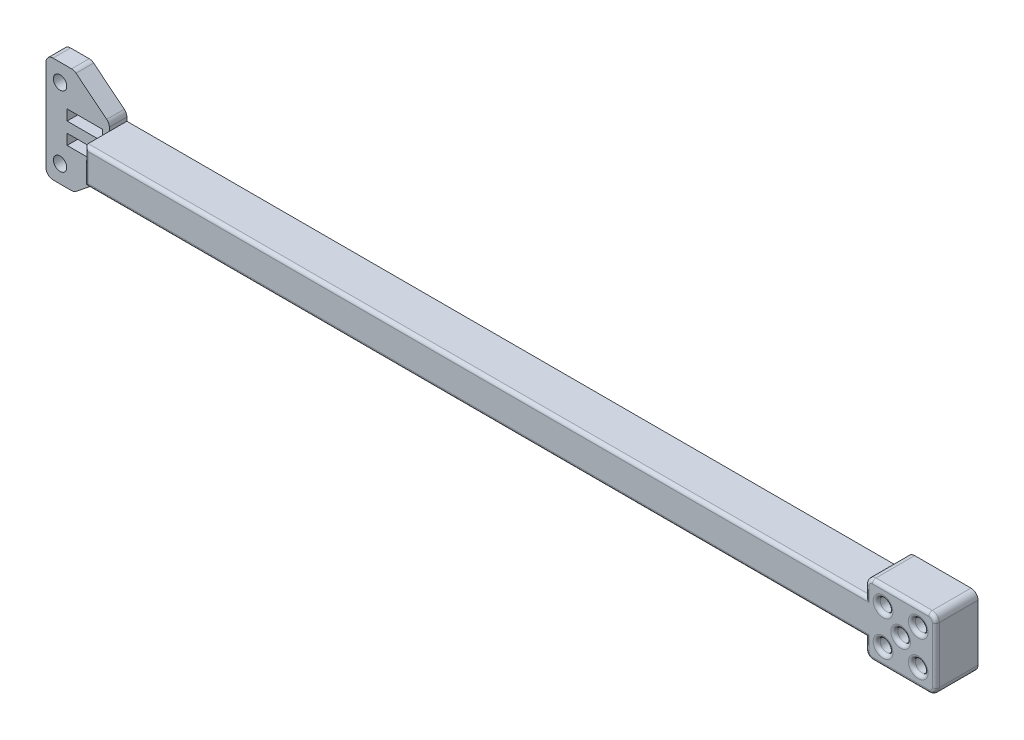
SolidWorks part; units mm, degrees
ref_plane "Front Plane" through (0, 0, 0) normal (0, 0, 1) x (1, 0, 0)
ref_plane "Top Plane" through (0, 0, 0) normal (0, 1, 0) x (1, 0, 0)
ref_plane "Right Plane" through (0, 0, 0) normal (1, 0, 0) x (0, 0, -1)
sketch "Sketch1" plane through (0, 0, 0) normal (0, 0, 1) x (1, 0, 0)
  line L0 (-140.97, -6.2865) -> (-140.97, -8.8265)
  line L1 (-140.97, -6.2865) -> (140.97, -6.2865)
  line L3 (-140.97, 6.2865) -> (140.97, 6.2865)
  line L5 (-163.83, 0) -> (153.67, 0) construction
  line L6 (-143.51, -1.905) -> (-143.51, -5.715)
  line L7 (-153.67, 19.05) -> (-163.83, 19.05)
  line L8 (-140.97, 8.8265) -> (-140.97, 6.2865)
  line L9 (-153.67, -19.05) -> (-163.83, -19.05)
  line L10 (-163.83, 19.05) -> (-163.83, -19.05)
  line L11 (-156.21, 1.905) -> (-143.51, 1.905)
  line L12 (-156.21, 1.905) -> (-156.21, 5.715)
  line L13 (-156.21, 5.715) -> (-143.51, 5.715)
  line L14 (-143.51, 1.905) -> (-143.51, 5.715)
  line L15 (-156.21, -5.715) -> (-143.51, -5.715)
  line L16 (-156.21, -1.905) -> (-143.51, -1.905)
  line L17 (-156.21, -1.905) -> (-156.21, -5.715)
  line L18 (-140.97, -8.8265) -> (-153.67, -19.05)
  line L19 (-140.97, 8.8265) -> (-153.67, 19.05)
  line L21 (166.37, -12.7) -> (140.97, -12.7)
  line L22 (166.37, -12.7) -> (166.37, 12.7)
  line L23 (166.37, 12.7) -> (140.97, 12.7)
  line L24 (140.97, -12.7) -> (140.97, 12.7)
  line L25 (166.37, -12.7) -> (140.97, 12.7) construction
  line L26 (166.37, 12.7) -> (140.97, -12.7) construction
  circle A1 centre (-158.75, -12.7) radius 2.413
  circle A4 centre (-158.75, 12.7) radius 2.413
  circle A5 centre (147.32, -6.35) radius 2.286
  circle A6 centre (160.02, -6.35) radius 2.286
  circle A7 centre (160.02, 6.35) radius 2.286
  circle A8 centre (147.32, 6.35) radius 2.286
  circle A9 centre (153.67, 0) radius 2.286
  point P0 (0, 0)
  point P4 (0, 6.2865)
  point P15 (-158.75, -19.05)
  point P18 (-163.83, 0)
  dimension "D3" = 4.826
  dimension "D8" = 6.35
  dimension "D9" = 25.4
  dimension "D19" = 4.572
  dimension "D2" = 38.1
  dimension "D4" = 12.7
  dimension "D5" = 10.16
  dimension "D6" = 317.5
  dimension "D7" = 12.573
  dimension "D10" = 5.08
  dimension "D11" = 3.81
  dimension "D12" = 12.7
  dimension "D13" = 1.905
  dimension "D14" = 7.62
  dimension "D15" = 2.54
  dimension "D16" = 22.86
  dimension "D17" = 25.4
  dimension "D18" = 6.35
  dimension "D20" = 2
  dimension "D21" = 2
extrude "Boss-Extrude1" add sketch "Sketch1" along normal blind 6.35
fillet "Fillet1" radius 2.54 10 edges at (-163.83, -19.05, 3.175) (-163.83, 19.05, 3.175) (-153.67, 19.05, 3.175) (-140.97, 8.8265, 3.175) (-140.97, -8.8265, 3.175) (-153.67, -19.05, 3.175) (140.97, 12.7, 3.175) (166.37, 12.7, 3.175) (166.37, -12.7, 3.175) (140.97, -12.7, 3.175)
sketch "Sketch3" plane through (0, 0, 6.35) normal (0, 0, 1) x (1, 0, 0)
  line L4 (-140.97, -6.2865) -> (-140.97, 6.2865)
  line L19 (140.97, -6.2865) -> (-140.97, -6.2865)
  line L20 (-140.97, 6.2865) -> (140.97, 6.2865)
  line L21 (140.97, 6.2865) -> (140.97, 10.16)
  line L22 (143.51, 12.7) -> (163.83, 12.7)
  line L23 (140.97, -10.16) -> (140.97, -6.2865)
  line L24 (163.83, -12.7) -> (143.51, -12.7)
  line L25 (166.37, 10.16) -> (166.37, -10.16)
  line L26 (140.97, -6.2865) -> (-140.97, -6.2865)
  line L27 (-140.97, 6.2865) -> (140.97, 6.2865)
  line L28 (140.97, 6.2865) -> (140.97, 10.16)
  line L29 (143.51, 12.7) -> (163.83, 12.7)
  line L30 (140.97, -10.16) -> (140.97, -6.2865)
  line L31 (163.83, -12.7) -> (143.51, -12.7)
  line L32 (166.37, 10.16) -> (166.37, -10.16)
  circle A4 centre (147.32, 6.35) radius 2.286
  circle A5 centre (153.67, 0) radius 2.286
  circle A6 centre (147.32, -6.35) radius 2.286
  circle A7 centre (160.02, 6.35) radius 2.286
  arc A8 (143.51, 12.7) -> (140.97, 10.16) centre (143.51, 10.16) ccw
  arc A9 (166.37, 10.16) -> (163.83, 12.7) centre (163.83, 10.16) ccw
  arc A10 (140.97, -10.16) -> (143.51, -12.7) centre (143.51, -10.16) ccw
  arc A11 (163.83, -12.7) -> (166.37, -10.16) centre (163.83, -10.16) ccw
  arc A12 (143.51, 12.7) -> (140.97, 10.16) centre (143.51, 10.16) ccw
  arc A13 (166.37, 10.16) -> (163.83, 12.7) centre (163.83, 10.16) ccw
  arc A14 (140.97, -10.16) -> (143.51, -12.7) centre (143.51, -10.16) ccw
  arc A15 (163.83, -12.7) -> (166.37, -10.16) centre (163.83, -10.16) ccw
  circle A16 centre (160.02, -6.35) radius 2.286
  circle A17 centre (147.32, 6.35) radius 2.286 construction
  dimension "D1" = 0
extrude "Boss-Extrude3" add sketch "Sketch3" along normal blind 8.89
sketch "Sketch5" plane through (0, 0, 0) normal (0, 1, 0) x (1, 0, 0)
  line L0 (-149.86, 0) -> (-149.86, -7.62) construction
  line L3 (-156.21, 0) -> (-143.51, 0) construction
  circle A0 centre (-149.86, -7.62) radius 5.08
  dimension "D1" = 7.62
  dimension "D2" = 10.16
extrude "Cut-Extrude1" [suppressed] cut sketch "Sketch5" against normal mid plane 16.51
ref_plane "Plane1" through (0, 0, 1.5875) normal (0, 0, -1) x (-1, 0, 0)
sketch "Sketch7" plane through (0, 0, 0) normal (0, 0, -1) x (-1, 0, 0)
  circle A0 centre (-147.32, 6.35) radius 4.445
  circle A1 centre (-160.02, 6.35) radius 4.445
  circle A2 centre (-160.02, -6.35) radius 4.445
  circle A3 centre (-147.32, -6.35) radius 4.445
  dimension "D1" = 8.89
  dimension "D2" = 2
  dimension "D3" = 2
extrude "Cut-Extrude2" cut sketch "Sketch7" against normal blind 2.54
fillet "Fillet3" radius 1.27 17 edges at (-140.97, 0, 15.24) (162.306, -6.35, 15.24) (149.606, -6.35, 15.24) (149.606, 6.35, 15.24) (140.97, 8.2233, 15.24) (141.7139, 11.9561, 15.24) (153.67, 12.7, 15.24) (165.6261, 11.9561, 15.24) (166.37, 0, 15.24) (165.6261, -11.9561, 15.24) (153.67, -12.7, 15.24) (141.7139, -11.9561, 15.24) (140.97, -8.2232, 15.24) (0, -6.2865, 15.24) (0, 6.2865, 15.24) (155.956, 0, 15.24) (162.306, 6.35, 15.24)
